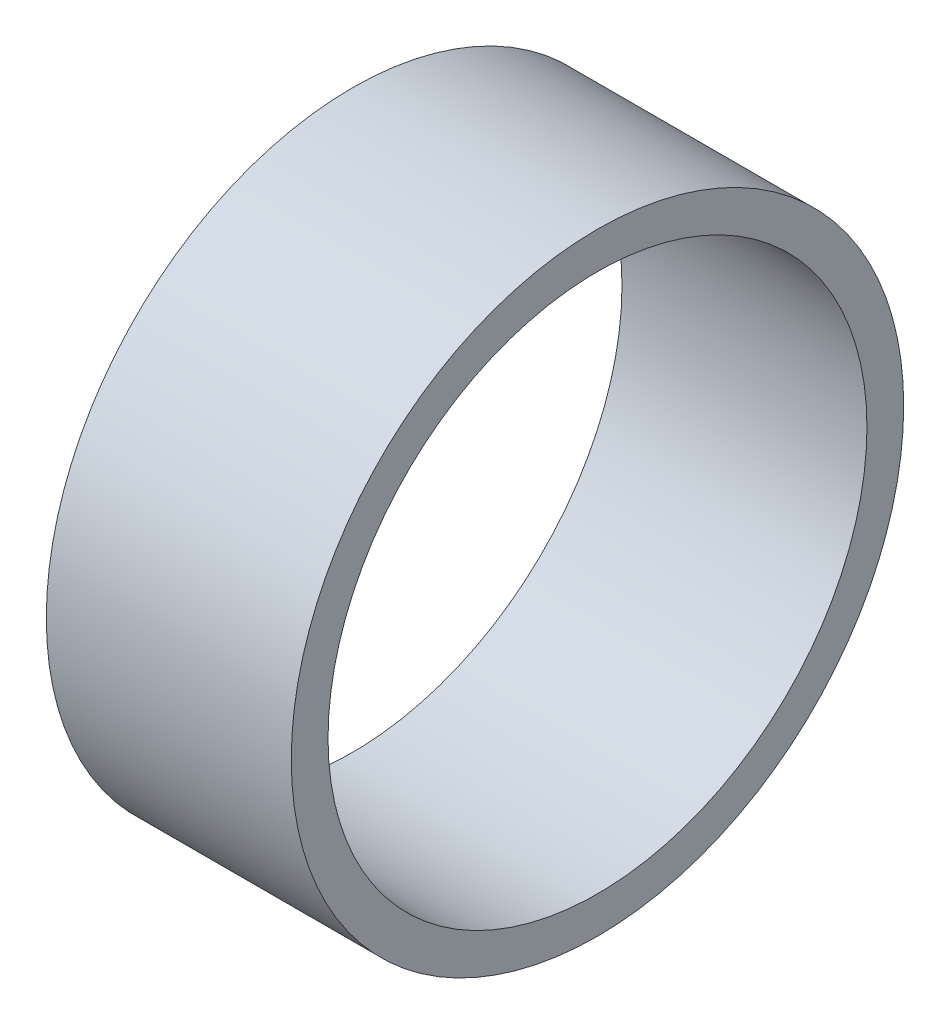
SolidWorks part; units mm, degrees
material "Rubber"
ref_plane "Front Plane" through (0, 0, 0) normal (0, 0, 1) x (1, 0, 0)
ref_plane "Top Plane" through (0, 0, 0) normal (0, 1, 0) x (1, 0, 0)
ref_plane "Right Plane" through (0, 0, 0) normal (1, 0, 0) x (0, 0, -1)
sketch "Sketch1" plane through (0, 0, 0) normal (0, 0, 1) x (1, 0, 0)
  line L0 (-45.4224, 0) -> (50.609, 0) construction
  line L1 (0, 57.7603) -> (0, -52.7308) construction
  line L2 (-20, 50) -> (-20, 44)
  line L3 (-20, 44) -> (20, 44)
  line L4 (20, 44) -> (20, 50)
  line L5 (20, 50) -> (-20, 50)
  dimension "D1" = 44
  dimension "D2" = 6
  dimension "D3" = 20
  dimension "D4" = 20
revolve "Revolve1" add sketch "Sketch1" angle 360 about L0
